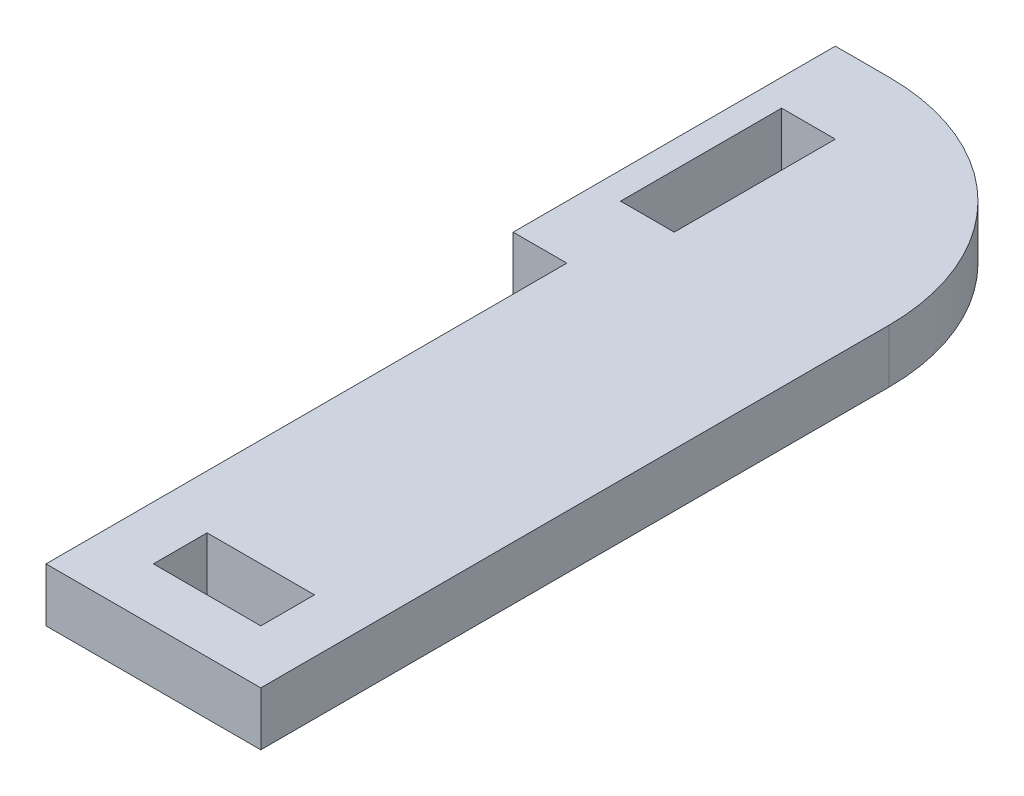
SolidWorks part; units mm, degrees
ref_plane "Front Plane" through (0, 0, 0) normal (0, 0, 1) x (1, 0, 0)
ref_plane "Top Plane" through (0, 0, 0) normal (0, 1, 0) x (1, 0, 0)
ref_plane "Right Plane" through (0, 0, 0) normal (1, 0, 0) x (0, 0, -1)
sketch "Sketch1" plane through (0, 0, 0) normal (0, 1, 0) x (1, 0, 0)
  line L9 (-20.0645, 67.5272) -> (-10.0645, 67.5272)
  line L10 (-20.0645, 67.5272) -> (-20.0645, 72.5272)
  line L11 (-20.0645, 72.5272) -> (-10.0645, 72.5272)
  line L12 (-10.0645, 67.5272) -> (-10.0645, 72.5272)
  line L14 (-30.0645, 111.0272) -> (-25.0645, 111.0272)
  line L15 (-30.0645, 111.0272) -> (-30.0645, 141.0272)
  line L19 (-25.0645, 62.5272) -> (-5.0645, 62.5272)
  line L24 (-27.5645, 118.5272) -> (-22.5645, 118.5272)
  line L25 (-27.5645, 118.5272) -> (-27.5645, 133.5272)
  line L26 (-27.5645, 133.5272) -> (-22.5645, 133.5272)
  line L27 (-22.5645, 118.5272) -> (-22.5645, 133.5272)
  line L29 (-5.0645, 141.0272) -> (-5.0645, 62.5272)
  line L31 (-30.0645, 141.0272) -> (-5.0645, 141.0272)
  line L32 (-25.0645, 62.5272) -> (-25.0645, 111.0272)
  point P14 (-27.5645, 120.0272)
  dimension "D2" = 5
  dimension "D5" = 5
  dimension "D7" = 5
  dimension "D10" = 30
  dimension "D14" = 15
  dimension "D15" = 2.5
  dimension "D17" = 46
  dimension "D18" = 7.5
extrude "Boss-Extrude1" add sketch "Sketch1" along normal blind 5
fillet "Fillet2" radius 20 1 edges at (-5.0645, 2.5, -141.0272)
